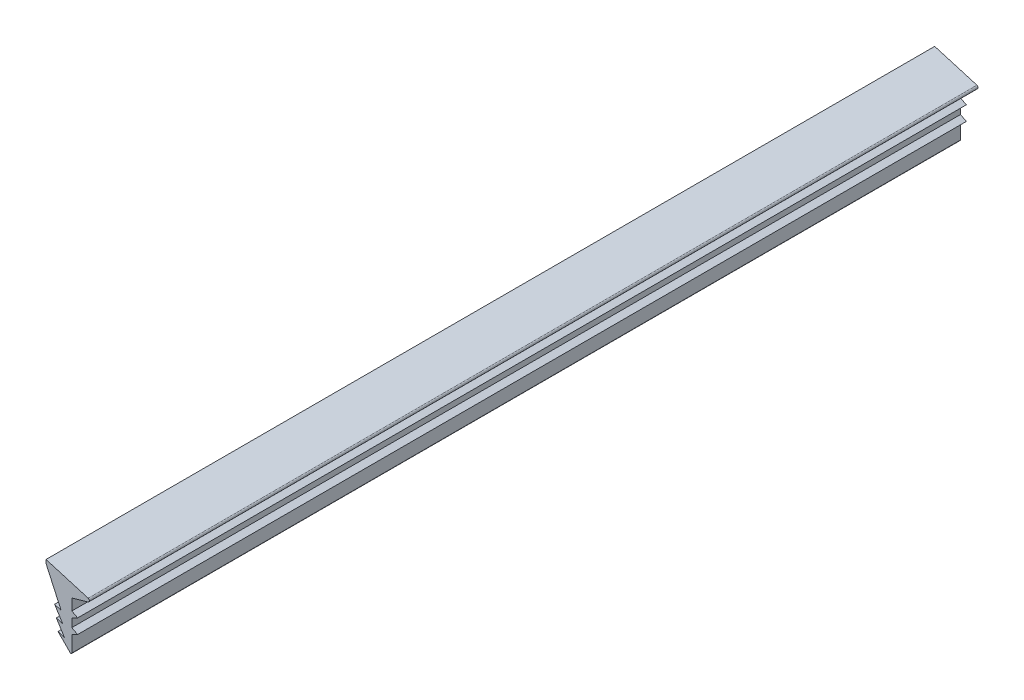
SolidWorks part; units mm, degrees
ref_plane "前视基准面" through (0, 0, 0) normal (0, 0, 1) x (1, 0, 0)
ref_plane "上视基准面" through (0, 0, 0) normal (0, 1, 0) x (1, 0, 0)
ref_plane "右视基准面" through (0, 0, 0) normal (1, 0, 0) x (0, 0, -1)
sketch "草图1" plane through (0, 0, 0) normal (0, 0, 1) x (1, 0, 0)
  line B0 (1.9105, 6.358) -> (-2.8382, 7.7571)
  line B1 (0.062, 2.5619) -> (0.062, 3.5126)
  line B2 (0.062, 4.1814) -> (0.062, 5.461)
  line B3 (0.062, 1.8932) -> (0.062, 0.0925)
  line B4 (0.062, 5.461) -> (1.8902, 5.9801)
  line B5 (0.062, 4.1814) -> (0.7258, 3.847)
  line B6 (0.062, 3.5126) -> (0.7258, 3.847)
  line B7 (0.062, 2.5619) -> (0.7258, 2.2276)
  line B8 (0.062, 1.8932) -> (0.7258, 2.2276)
  line B9 (-0.1091, 0.0222) -> (-1.4838, 1.4125)
  line B10 (-1.4838, 1.4125) -> (-0.7491, 1.1624)
  line B11 (-0.7491, 1.1624) -> (-1.6751, 2.6468)
  line B12 (-1.6751, 2.6468) -> (-0.9404, 2.3967)
  line B13 (-0.9404, 2.3967) -> (-1.8664, 3.8811)
  line B14 (-1.8664, 3.8811) -> (-1.1317, 3.631)
  line B15 (-1.1317, 3.631) -> (-2.8382, 7.3736)
  line B16 (-2.8382, 7.3736) -> (-2.8382, 7.7571)
  arc B17 (1.8902, 5.9801) -> (1.9105, 6.358) centre (1.8356, 6.1725) ccw
  arc B18 (-0.1091, 0.0222) -> (0.062, 0.0925) centre (-0.038, 0.0925) ccw
sketch_block_instance "A$C17485B6B-1"
sketch_block "A$C17485B6B"
extrude "凸台-拉伸1" add sketch "草图1" along normal blind 100
